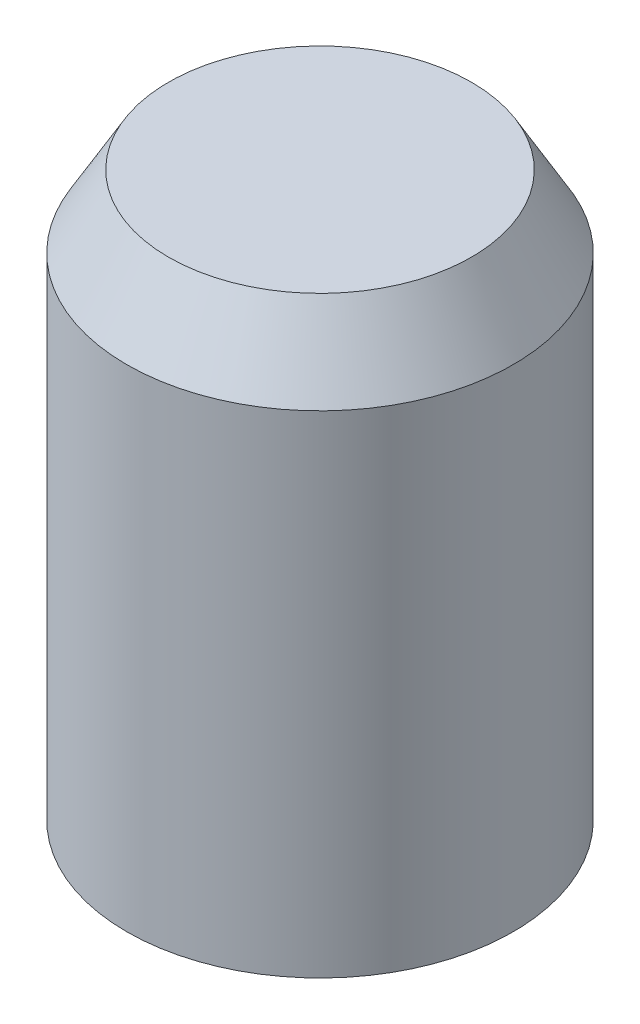
SolidWorks part; units mm, degrees
ref_plane "Front Plane" through (0, 0, 0) normal (0, 0, 1) x (1, 0, 0)
ref_plane "Top Plane" through (0, 0, 0) normal (0, 1, 0) x (1, 0, 0)
ref_plane "Right Plane" through (0, 0, 0) normal (1, 0, 0) x (0, 0, -1)
sketch "Sketch1" plane through (0, 0, 0) normal (0, 1, 0) x (1, 0, 0)
  circle A0 centre (0, 0) radius 13.375
  dimension "D1" = 26.75
extrude "Boss-Extrude1" add sketch "Sketch1" along normal blind 39
chamfer "Chamfer1" distance 5 angle 30 1 edges at (0, 39, 13.375)
